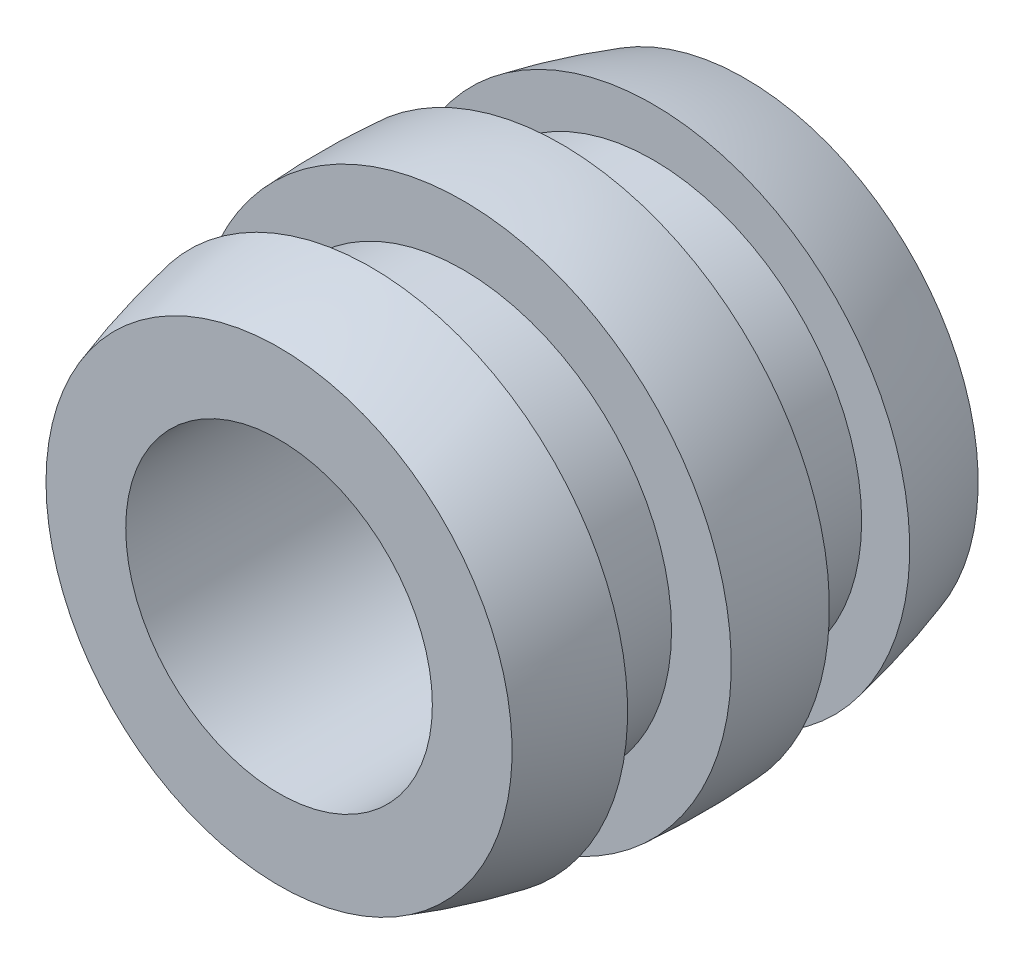
SolidWorks part; units mm, degrees
ref_plane "Front Plane" through (0, 0, 0) normal (0, 0, 1) x (1, 0, 0)
ref_plane "Top Plane" through (0, 0, 0) normal (0, 1, 0) x (1, 0, 0)
ref_plane "Right Plane" through (0, 0, 0) normal (1, 0, 0) x (0, 0, -1)
sketch "Sketch2" plane through (0, 0, 0) normal (1, 0, 0) x (0, 0, -1)
  line L1 (12.065, 0) -> (-12.065, 0)
  line L2 (-12.065, 0) -> (-12.065, 12.065)
  line L3 (-7.3025, 13.2831) -> (-7.3025, 10.795)
  line L4 (-7.3025, 10.795) -> (-2.54, 10.795)
  line L5 (-2.54, 10.795) -> (-2.54, 13.8875)
  line L6 (0, 0) -> (0, 13.97) construction
  line L7 (12.065, 0) -> (12.065, 12.065)
  line L8 (2.54, 10.795) -> (2.54, 13.8875)
  line L9 (7.3025, 10.795) -> (2.54, 10.795)
  line L10 (7.3025, 13.2831) -> (7.3025, 10.795)
  arc A0 (12.065, 12.065) -> (7.3025, 13.2831) centre (0, -25.1883) ccw
  arc A1 (-7.3025, 13.2831) -> (-12.065, 12.065) centre (0, -25.1883) ccw
  arc A2 (2.54, 13.8875) -> (-2.54, 13.8875) centre (0, -25.1883) ccw
  dimension "D1" = 24.13
  dimension "D2" = 4.7625
  dimension "D3" = 4.7625
  dimension "D4" = 12.065
  dimension "D5" = 13.97
  dimension "D6" = 10.795
revolve "Revolve1" add sketch "Sketch2" angle 360 about L1
sketch "Sketch3" plane through (0, 0, 0) normal (0, 0, 1) x (1, 0, 0)
  circle A0 centre (0, 0) radius 7.9375
  dimension "D1" = 15.875
extrude "Cut-Extrude1" cut sketch "Sketch3" against normal through all both and the other way through all
